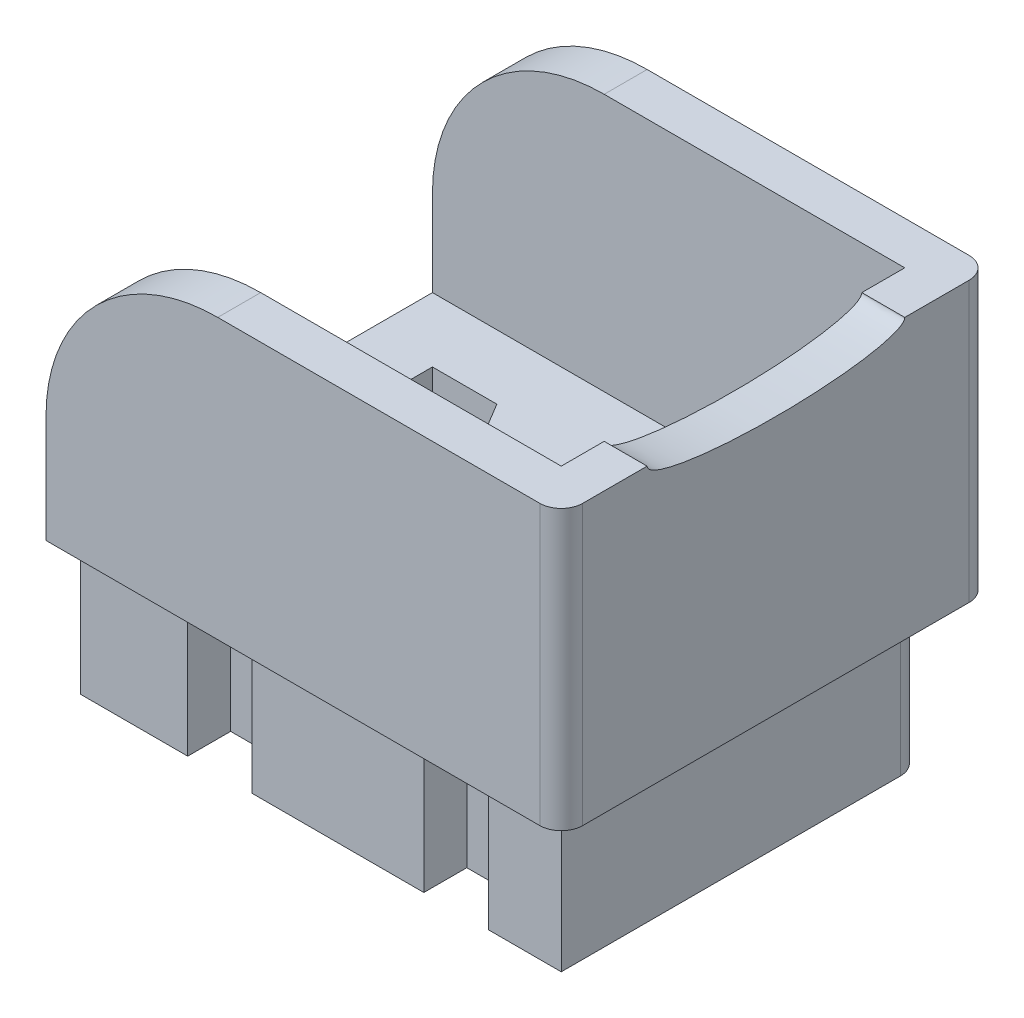
SolidWorks part; units mm, degrees
ref_plane "Front Plane" through (0, 0, 0) normal (0, 0, 1) x (1, 0, 0)
ref_plane "Top Plane" through (0, 0, 0) normal (0, 1, 0) x (1, 0, 0)
ref_plane "Right Plane" through (0, 0, 0) normal (1, 0, 0) x (0, 0, -1)
sketch "Sketch3" plane through (0, 0, 0) normal (0, 1, 0) x (1, 0, 0)
  line L0 (-5, 0.75) -> (0, 1.05) construction
  line L3 (0, -1.05) -> (-5, -0.75) construction
  line L4 (-2.5, 0.9) -> (-2, 0.93)
  line L6 (-4.25, 0) -> (-5.75, 0) construction
  line L7 (-2, 0.93) -> (-2, 0.56)
  line L8 (-2.5, 0.9) -> (-5, 0.9) construction
  line L9 (-2.5, 0.9) -> (-2.5, -0.9)
  line L10 (-2.5, -0.9) -> (-5, -0.9) construction
  line L11 (-5, 0.9) -> (-5, -0.9) construction
  line L12 (-2, 0.96) -> (-1.5, 0.96) construction
  line L13 (-2, 0.96) -> (-2, 0.56) construction
  line L14 (-2, 0.56) -> (-1.5, 0.56)
  line L15 (-1.5, 0.96) -> (-1.5, 0.56)
  line L16 (-1.5, -0.56) -> (-2, -0.56)
  line L17 (-1.5, -0.56) -> (-1.5, -0.96)
  line L18 (-1.5, -0.96) -> (-2, -0.96) construction
  line L19 (-2, -0.56) -> (-2, -0.96) construction
  line L21 (-2.5, -0.9) -> (-2, -0.93)
  line L22 (-2, -0.93) -> (-2, -0.56)
  line L23 (-1.5, 0.96) -> (0, 1.05)
  line L24 (0, -1.05) -> (-1.5, -0.96)
  circle A2 centre (0, 0) radius 0.6 construction
  circle A3 centre (0, 0) radius 0.4 construction
  circle A4 centre (-5, 0) radius 0.35 construction
  circle A5 centre (0, 0) radius 1.05 construction
  circle A6 centre (-5, 0) radius 0.75 construction
  arc A7 (-5, 0.9) -> (-5, -0.9) centre (-5, 0) ccw construction
  arc A8 (0, 1.05) -> (0, -1.05) centre (0, 0) cw
  point P4 (-2, -0.93)
  point P15 (-5, 0)
  point P16 (-2, 0.93)
  point P22 (-5, 0)
  dimension "D2" = 1.2
  dimension "D3" = 0.8
  dimension "D4" = 0.7
  dimension "D6" = 5
  dimension "D1" = 1.5
  dimension "D5" = 2.1
  dimension "D7" = 0.4
  dimension "D9" = 2.5
  dimension "D10" = 1.8
  dimension "D11" = 2.5
  dimension "D12" = 0.5
  dimension "D14" = 1.5
sketch "Sketch5" plane through (0, 0, 0) normal (0, 1, 0) x (1, 0, 0)
  line L0 (-2.25, 0) -> (1.75, 0) construction
  line L1 (-2.25, -2) -> (1.75, -2)
  line L2 (-2.25, -2) -> (-2.25, 2)
  line L3 (-2.25, 2) -> (1.75, 2)
  line L4 (1.75, -2) -> (1.75, 2) construction
  line L5 (-2.25, -2) -> (1.75, 2) construction
  line L6 (-2.25, 2) -> (1.75, -2) construction
  line L8 (1.75, 2) -> (3.25, 2)
  line L9 (3.25, 2) -> (3.25, -2)
  line L10 (3.25, -2) -> (1.75, -2)
  circle A1 centre (0, 0) radius 0.125 construction
  point P1 (-0.25, 0)
  dimension "D2" = 0.25
  dimension "D1" = 1.75
  dimension "D3" = 4
  dimension "D4" = 1.5
  dimension "D5" = 4
extrude "Boss-Extrude2" add sketch "Sketch5" against normal blind 2
sketch "Sketch6" plane through (0, 0, 0) normal (0, 0, 1) x (1, 0, 0)
  line L0 (3.25, 0.5) -> (3.25, 1.75)
  line L1 (3.25, 1.75) -> (1.75, 2.25)
  line L2 (1.75, 2.25) -> (1.75, 0.5)
  line L3 (1.75, 0.5) -> (3.25, 0.5)
  line L4 (2.5, 2) -> (2.1349, 0.9047)
  line L5 (1.75, 0.5) -> (1.75, 0) construction
  line L6 (3.25, 0.5) -> (3.25, 0) construction
  line L7 (1.75, 0) -> (3.25, 0) construction
  dimension "D1" = 1.25
  dimension "D2" = 1.75
  dimension "D3" = 0.5
ref_plane "Plane1" through (0.85, 2.55, 0) normal (0.3162, 0.9487, 0) x (0.9487, -0.3162, 0)
sketch "Sketch8" plane through (0.85, 2.55, 0) normal (0.3162, 0.9487, 0) x (0.9487, -0.3162, 0)
  line L0 (2.5298, 0) -> (0.9487, 0) construction
  line L2 (2.5298, 0) -> (1.8298, 0) construction
  circle A0 centre (1.8298, 0) radius 0.46
  dimension "D1" = 0.92
  dimension "D2" = 0.7
extrude "Cut-Extrude1" cut sketch "Sketch8" against normal through all
sketch "Sketch12" plane through (0, 0, 0) normal (0, 1, 0) x (1, 0, 0)
  line L0 (-2.25, 0) -> (1.75, 0) construction
  line L2 (-1.5, 1.25) -> (-1.5, -1.25)
  line L8 (-1.5, 0) -> (0, 0) construction
  line L9 (-1.5, -1.25) -> (-0.75, -1.25)
  line L10 (-0.75, -1.25) -> (0, 0)
  line L11 (0, 0) -> (-0.75, 1.25)
  line L12 (-0.75, 1.25) -> (-1.5, 1.25)
  dimension "D1" = 2.5
  dimension "D2" = 1.5
  dimension "D3" = 0.75
  dimension "D4" = 0.75
extrude "Cut-Extrude3" cut sketch "Sketch12" against normal through all
sketch "Sketch10" plane through (0, 0, 2) normal (0, 0, 1) x (1, 0, 0)
  line L0 (3.25, -2) -> (3.25, 3)
  line L1 (3.25, 3) -> (-2.25, 3)
  line L2 (-2.25, 3) -> (-2.25, 0)
  line L3 (-2.25, 0) -> (-2.25, -2)
  line L4 (-2.25, -2) -> (3.25, -2)
  dimension "D1" = 5
extrude "Boss-Extrude3" add sketch "Sketch10" along normal blind 0.5
mirror "Mirror1" about plane through (0, 0, 0) normal (0, 0, 1) of "Boss-Extrude3"
sketch "Sketch11" plane through (3.25, 0, 0) normal (1, 0, 0) x (0, 0, -1)
  line L0 (-2.5, 3) -> (2.5, 3)
  line L1 (2.5, 3) -> (2.5, -2)
  line L2 (2.5, -2) -> (-2.5, -2)
  line L3 (-2.5, -2) -> (-2.5, 3)
extrude "Boss-Extrude4" add sketch "Sketch11" along normal blind 0.5
fillet "Fillet1" radius 2 2 edges at (-2.25, 3, -2.25) (-2.25, 3, 2.25)
sketch "Sketch14" plane through (0, -2, 0) normal (0, -1, 0) x (1, 0, 0)
  line L0 (-2.25, 2.5) -> (-2.25, 2.1)
  line L1 (-2.25, -2.5) -> (-2.25, 2.5) construction
  line L2 (-2.25, 2.1) -> (3.35, 2.1)
  line L3 (3.35, 2.1) -> (3.35, -2.1)
  line L4 (3.35, -2.1) -> (-2.25, -2.1)
  line L5 (-2.25, -2.1) -> (-2.25, -2.5)
  line L6 (-2.25, -2.5) -> (3.75, -2.5)
  line L7 (3.75, -2.5) -> (3.75, 2.5)
  line L8 (3.75, 2.5) -> (-2.25, 2.5)
  line L9 (3.35, 0) -> (3.75, 0) construction
  line L10 (-2.25, 2) -> (1.75, 2) construction
  dimension "D1" = 0.1
extrude "Cut-Extrude5" cut sketch "Sketch14" against normal blind 1.75
sketch "Sketch13" plane through (0, 0, 2.1) normal (0, 0, 1) x (1, 0, 0)
  line L1 (-2.25, -2) -> (3.75, -2) construction
  line L7 (-0.625, -2) -> (2.125, -2) construction
  line L9 (-0.25, -0.25) -> (-1, -0.25)
  line L10 (-1, -0.25) -> (-1, -2)
  line L11 (-1, -2) -> (-0.25, -2)
  line L12 (-0.25, -2) -> (-0.25, -0.25)
  line L14 (2.5, -0.25) -> (1.75, -0.25)
  line L15 (1.75, -0.25) -> (1.75, -2)
  line L16 (1.75, -2) -> (2.5, -2)
  line L17 (2.5, -2) -> (2.5, -0.25)
  point P1 (0.75, -2)
  dimension "D1" = 0.75
  dimension "D2" = 1.75
  dimension "D3" = 2
extrude "Cut-Extrude4" cut sketch "Sketch13" against normal blind 0.5
mirror "Mirror2" about plane through (0, 0, 0) normal (0, 0, 1) of "Cut-Extrude4"
fillet "Fillet2" radius 0.25 8 edges at (3.35, -1.125, -2.1) (-1.625, -0.25, -2.1) (0.75, -0.25, -2.1) (2.925, -0.25, -2.1) (3.35, -0.25, 0) (2.925, -0.25, 2.1) (0.75, -0.25, 2.1) (-1.625, -0.25, 2.1)
fillet "Fillet3" radius 0.25 2 edges at (3.75, 1.375, -2.5) (3.75, 1.375, 2.5)
sketch "Sketch15" plane through (3.75, 0, 0) normal (1, 0, 0) x (0, 0, -1)
  line L0 (2.25, 3) -> (-2.25, 3) construction
  ellipse E0 centre (0, 3) end of major axis (1.5, 3) minor radius 0.25
  dimension "D1" = 1.5
  dimension "D2" = 0.25
extrude "Cut-Extrude6" cut sketch "Sketch15" against normal through all
